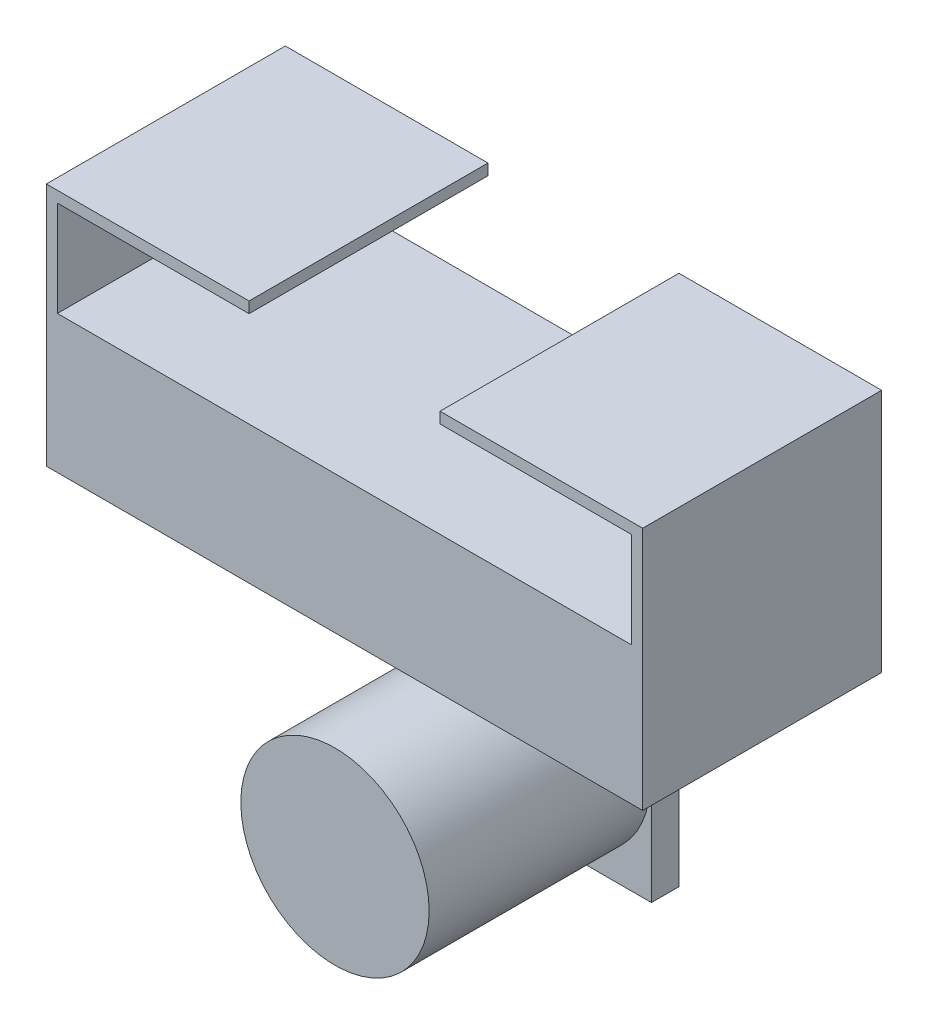
SolidWorks part; units mm, degrees
material "ASTM A36 Steel"
ref_plane "Front Plane" through (0, 0, 0) normal (0, 0, 1) x (1, 0, 0)
ref_plane "Top Plane" through (0, 0, 0) normal (0, 1, 0) x (1, 0, 0)
ref_plane "Right Plane" through (0, 0, 0) normal (1, 0, 0) x (0, 0, -1)
sketch "Sketch1" plane through (0, 0, 0) normal (0, 0, 1) x (1, 0, 0)
  circle A0 centre (0, 0) radius 12.5124
  dimension "D1" = 25.0249
extrude "Boss-Extrude1" add sketch "Sketch1" along normal blind 33.02
sketch "Sketch9" plane through (0, 0, 0) normal (0, 0, -1) x (-1, 0, 0)
  line L0 (-12.7, -13.6153) -> (12.7, -13.6153)
  line L1 (12.7, -13.6153) -> (12.7, 24.4847)
  line L2 (12.7, 24.4847) -> (-12.7, 24.4847)
  line L3 (-12.7, 24.4847) -> (-12.7, -13.6153)
  line L4 (0, 24.4847) -> (0, -13.6153) construction
  line L5 (0, 0) -> (0, 12.5124) construction
  line L6 (-12.5124, 0) -> (12.5124, 0) construction
  circle A0 centre (0, 0) radius 12.5124 construction
  dimension "D2" = 38.1
extrude "Boss-Extrude2" add sketch "Sketch9" against normal blind 3.6678
sketch "Sketch10" plane through (0, 24.4847, 0) normal (0, 1, 0) x (1, 0, 0)
  line L1 (-38.1508, 0) -> (38.1508, 0)
  line L2 (-38.1508, 0) -> (-38.1508, -31.75)
  line L3 (-38.1508, -31.75) -> (38.1508, -31.75)
  line L4 (38.1508, 0) -> (38.1508, -31.75)
  line L6 (0, 0) -> (0, -33.02) construction
  line L7 (-12.5124, -33.02) -> (12.5124, -33.02) construction
  line L8 (0, 0) -> (0, -31.75) construction
  line L9 (-12.7, 0) -> (12.7, 0) construction
  dimension "D1" = 31.75
  dimension "D2" = 76.3016
extrude "Boss-Extrude3" add sketch "Sketch10" along normal blind 18.3162
sketch "Sketch13" plane through (0, 0, 31.75) normal (0, 0, 1) x (1, 0, 0)
  line L0 (0, 12.5124) -> (0, 132.4224) construction
  line L1 (-38.1508, 24.4847) -> (-39.6184, 24.4847)
  line L2 (-38.1508, 24.4847) -> (-38.1508, 56.968)
  line L3 (-38.1508, 56.968) -> (-39.6184, 56.968)
  line L4 (-39.6184, 24.4847) -> (-39.6184, 56.968)
  line L5 (38.1508, 56.968) -> (39.6184, 56.968)
  line L6 (39.6184, 24.4847) -> (39.6184, 56.968)
  line L7 (38.1508, 24.4847) -> (39.6184, 24.4847)
  line L8 (38.1508, 24.4847) -> (38.1508, 56.968)
  circle A0 centre (0, 0) radius 12.5124 construction
  dimension "D1" = 32.4833
  dimension "D2" = 1.4676
extrude "Boss-Extrude4" add sketch "Sketch13" against normal blind 31.75
sketch "Sketch14" plane through (0, 56.968, 0) normal (0, 1, 0) x (1, 0, 0)
  line L0 (-38.1508, -31.75) -> (38.1508, -31.75) construction
  line L1 (-38.1508, 0) -> (-12.6873, 0)
  line L2 (-38.1508, 0) -> (-38.1508, -31.75)
  line L3 (-38.1508, -31.75) -> (-12.6873, -31.75)
  line L4 (-12.6873, 0) -> (-12.6873, -31.75)
  line L5 (0, -31.75) -> (0, 9.9154) construction
  line L6 (38.1508, -31.75) -> (12.6873, -31.75)
  line L7 (12.6873, 0) -> (12.6873, -31.75)
  line L8 (38.1508, 0) -> (12.6873, 0)
  line L9 (38.1508, 0) -> (38.1508, -31.75)
extrude "Boss-Extrude5" add sketch "Sketch14" against normal blind 1.4671
equation "\"P\"= 650'lbf"
equation "\"SF\"= 4'Safety Factor"
equation "\"E\"= 29000000'Elasticity (psi)"
equation "\"SY\"= 36000'Yield Strength (psi)"
equation "\"def\"= 0.005in'Max Deflection (in)"
equation "\"W\"= \"P\" * 2'2 times the force"
equation "\"LA\"= 1.30'Length A"
equation "\"ZA\"= ( \"SF\" * \"W\" * \"LA\" ) / ( 2 * \"SY\" )'in^3"
equation "\"RA\"= ( 4 * ( \"ZA\" / pi ) ) ^ ( 1 / 3 )'Radius A"
equation "\"DA\"= \"RA\" * 2in'Diameter A"
equation "\"wb\"= 1in'Width B"
equation "\"hb\"= 1.5in'Height B"
equation "\"tb\"= ( 0.1444in / 1.00in )'Thickness B"
equation "\"lc\"= 3in + 0.004in'Minimum Length of C with RC7"
equation "\"wc\"= 1.25in'Width C"
equation "\"ic\"= ( 5 * \"W\" * \"SF\" * ( \"lc\" ^ 4 ) ) / ( 384 * \"E\" * \"def\" )'in^4"
equation "\"hc\"= ( sqr ( 0.52in ) )'Height C"
equation "\"hd\"= 0.498in + 0.002'Minimum Height of D with RC7"
equation "\"wd\"= 1.25in'Width D"
equation "\"Ad\"= ( 650in / 9000 )'Area D (in^2)"
equation "\"ld\"= \"Ad\" / \"wd\"'Length D"
equation "\"le\"= 1in + 0.0025in'Minimum Length of E with RC7"
equation "\"we\"= 1.25in'Width E"
equation "\"he\"= ( 0.0722in / 1.25 )'Height E"
equation "\"D1@Sketch1\"=\"DA\""
equation "\"D1@Boss-Extrude1\"=\"LA\""
equation "\"D1@Sketch9\"=\"wb\""
equation "\"D2@Sketch9\"=\"hb\""
equation "\"D1@Boss-Extrude2\"=\"tb\""
equation "\"D1@Sketch10\"=\"wc\""
equation "\"D2@Sketch10\"=\"lc\""
equation "\"D1@Boss-Extrude3\"=\"hc\""
equation "\"sr\"= \"hc\" + \"hd\" + \"he\"'height of side rectangles"
equation "\"D1@Sketch13\"=\"sr\""
equation "\"D2@Sketch13\"=\"ld\""
equation "\"D1@Boss-Extrude4\"=\"wd\""
equation "\"D1@Sketch14\"=\"le\""
equation "\"D1@Boss-Extrude5\"=\"he\""
